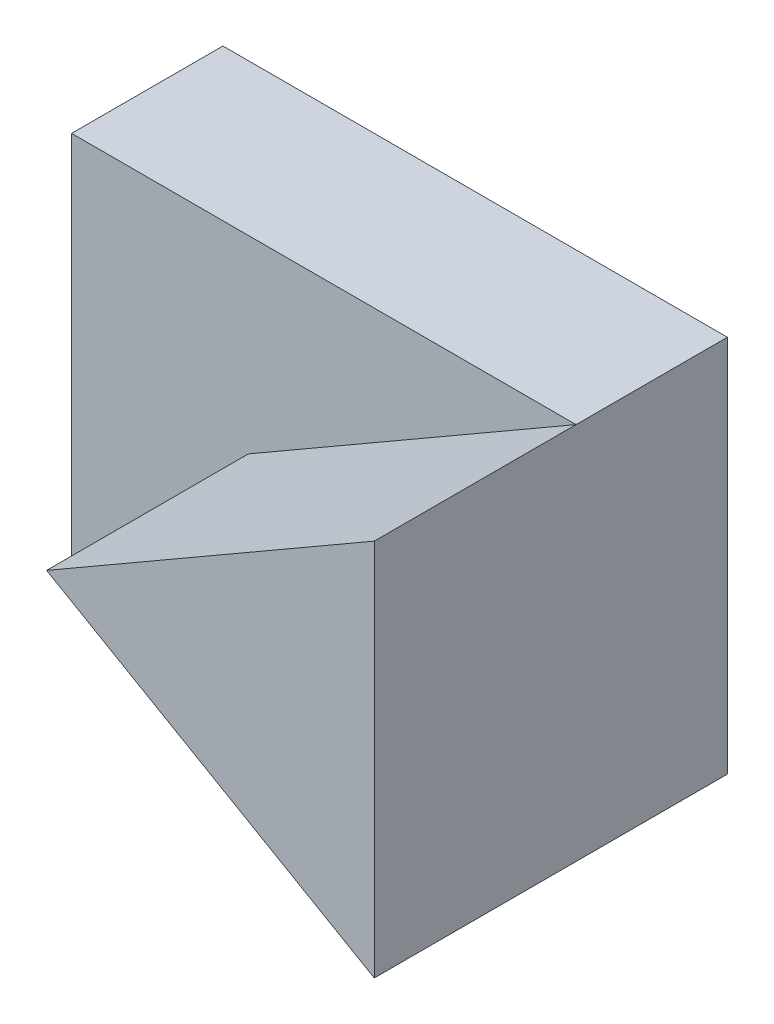
SolidWorks part; units mm, degrees
ref_plane "前视基准面" through (0, 0, 0) normal (0, 0, 1) x (1, 0, 0)
ref_plane "上视基准面" through (0, 0, 0) normal (0, 1, 0) x (1, 0, 0)
ref_plane "右视基准面" through (0, 0, 0) normal (1, 0, 0) x (0, 0, -1)
other "Configuration Table"
sketch "草图1" plane through (0, 0, 0) normal (0, 0, 1) x (1, 0, 0)
  line L1 (-17.0149, 15) -> (2.9851, 15)
  line L2 (-17.0149, 15) -> (-17.0149, 0)
  line L3 (-17.0149, 0) -> (2.9851, 0)
  line L4 (2.9851, 15) -> (2.9851, 0)
  line L5 (-17.0149, 15) -> (2.9851, 0) construction
  line L6 (-17.0149, 0) -> (2.9851, 15) construction
  point P0 (-7.0149, 7.5)
  dimension "D1" = 20
  dimension "D2" = 15
extrude "凸台-拉伸1" add sketch "草图1" along normal mid plane 6
sketch "草图2" plane through (0, 0, 3) normal (0, 0, 1) x (1, 0, 0)
  line L0 (2.9851, 0) -> (2.9851, 15) construction
  line L1 (2.9851, 0) -> (2.9851, 15)
  line L2 (2.9851, 15) -> (-10.0053, 7.5)
  line L3 (-10.0053, 7.5) -> (2.9851, 0)
  circle A0 centre (-1.3451, 7.5) radius 4.3301 construction
  point P7 (2.9851, 7.5)
  point P8 (0, 0)
extrude "凸台-拉伸2" add sketch "草图2" along normal blind 8 separate body
sketch3d "3D草图1"
  line L0 (-3.5101, 3.75, 11) -> (-7.0149, 0, 3)
  line L1 (-10.0053, 7.5, 11) -> (2.9851, 0, 11) construction
  line L2 (-17.0149, 0, 3) -> (2.9851, 0, 3) construction
  line L3 (-3.5101, 3.75, 11) -> (-3.5101, 3.75, 3)
  line L4 (-10.0053, 7.5, 3) -> (2.9851, 0, 3) construction
  line L5 (-3.5101, 3.75, 3) -> (-7.0149, 0, 3)
  point P6 (0, 0, 0)
  point P7 (-3.5101, 3.75, 11)
  point P8 (-7.0149, 0, 3)
  point P9 (-7.0149, 0, 3)
  point P10 (0, 0, 0)
  point P14 (-3.5101, 3.75, 3)
extrude "凸台-拉伸3" add sketch "3D草图1" along direction (0.866, -0.5, 0) on the side against the normal blind 1 contours L0 L5 L3
